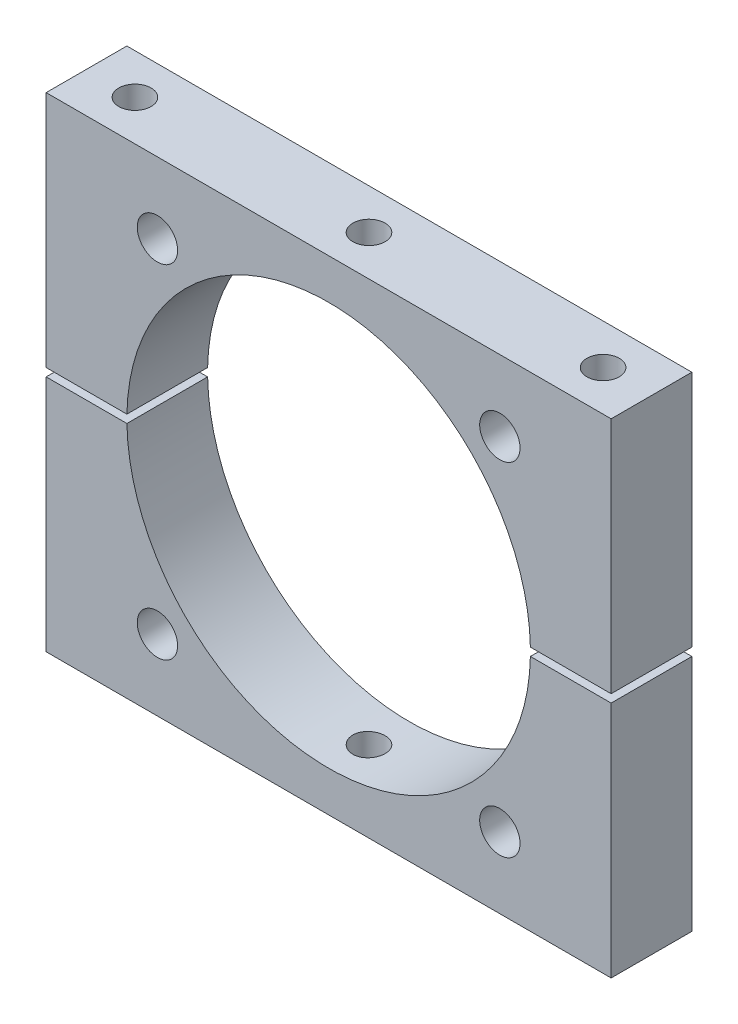
SolidWorks part; units mm, degrees
material "6061 Alloy"
ref_plane "Front Plane" through (0, 0, 0) normal (0, 0, 1) x (1, 0, 0)
ref_plane "Top Plane" through (0, 0, 0) normal (0, 1, 0) x (1, 0, 0)
ref_plane "Right Plane" through (0, 0, 0) normal (1, 0, 0) x (0, 0, -1)
sketch "Sketch1" plane through (0, 0, 0) normal (0, 0, 1) x (1, 0, 0)
  line L1 (0, 0) -> (70, 0)
  line L2 (0, 0) -> (0, 60)
  line L3 (0, 60) -> (70, 60)
  line L4 (70, 0) -> (70, 60)
  dimension "D1" = 60
  dimension "D2" = 70
extrude "Boss-Extrude1" add sketch "Sketch1" along normal blind 10
sketch "Sketch2" plane through (0, 0, 10) normal (0, 0, 1) x (1, 0, 0)
  line L0 (35, 60) -> (35, 0) construction
  line L1 (70, 60) -> (0, 60) construction
  line L2 (0, 0) -> (70, 0) construction
  line L3 (0, 30) -> (70, 30) construction
  line L4 (0, 60) -> (0, 0) construction
  line L5 (70, 0) -> (70, 60) construction
  line L6 (10.005, 30.5) -> (0, 30.5)
  line L7 (59.995, 30.5) -> (70, 30.5)
  line L8 (70, 30.5) -> (70, 29.5)
  line L9 (70, 29.5) -> (59.995, 29.5)
  line L10 (0, 29.5) -> (10.005, 29.5)
  line L11 (0, 29.5) -> (0, 30.5)
  arc A0 (10.005, 29.5) -> (59.995, 29.5) centre (35, 30) ccw
  arc A1 (59.995, 30.5) -> (10.005, 30.5) centre (35, 30) ccw
  point P22 (0, 30)
  dimension "D1" = 50
  dimension "D2" = 1
extrude "Cut-Extrude1" cut sketch "Sketch2" against normal blind 10
sketch "Sketch3" plane through (0, 60, 0) normal (0, 1, 0) x (1, 0, 0)
  line L0 (0, -5) -> (70, -5) construction
  line L1 (0, -10) -> (0, 0) construction
  line L2 (70, -10) -> (70, 0) construction
  line L3 (70, -10) -> (0, -10) construction
  circle A0 centre (6, -5) radius 2
  circle A1 centre (64, -5) radius 2
  circle A2 centre (35, -5) radius 2
  point P16 (35, -10)
  dimension "D1" = 4
  dimension "D2" = 4
  dimension "D4" = 6
  dimension "D5" = 4
  dimension "D3" = 6
extrude "Cut-Extrude2" cut sketch "Sketch3" against normal through all
sketch "Sketch6" plane through (0, 0, 10) normal (0, 0, 1) x (1, 0, 0)
  line L0 (0, 60) -> (70, 0) construction
  line L1 (0, 0) -> (70, 60) construction
  line L2 (35, 30) -> (13.7868, 51.2132) construction
  line L3 (0, 29.5) -> (10.005, 29.5) construction
  circle A0 centre (13.7868, 51.2132) radius 2.5
  circle A1 centre (56.2132, 51.2132) radius 2.5
  circle A2 centre (56.2132, 8.7868) radius 2.5
  circle A3 centre (13.7868, 8.7868) radius 2.5
  dimension "D3" = 45
  dimension "D1" = 5
  dimension "D2" = 30
extrude "Cut-Extrude3" cut sketch "Sketch6" against normal through all
